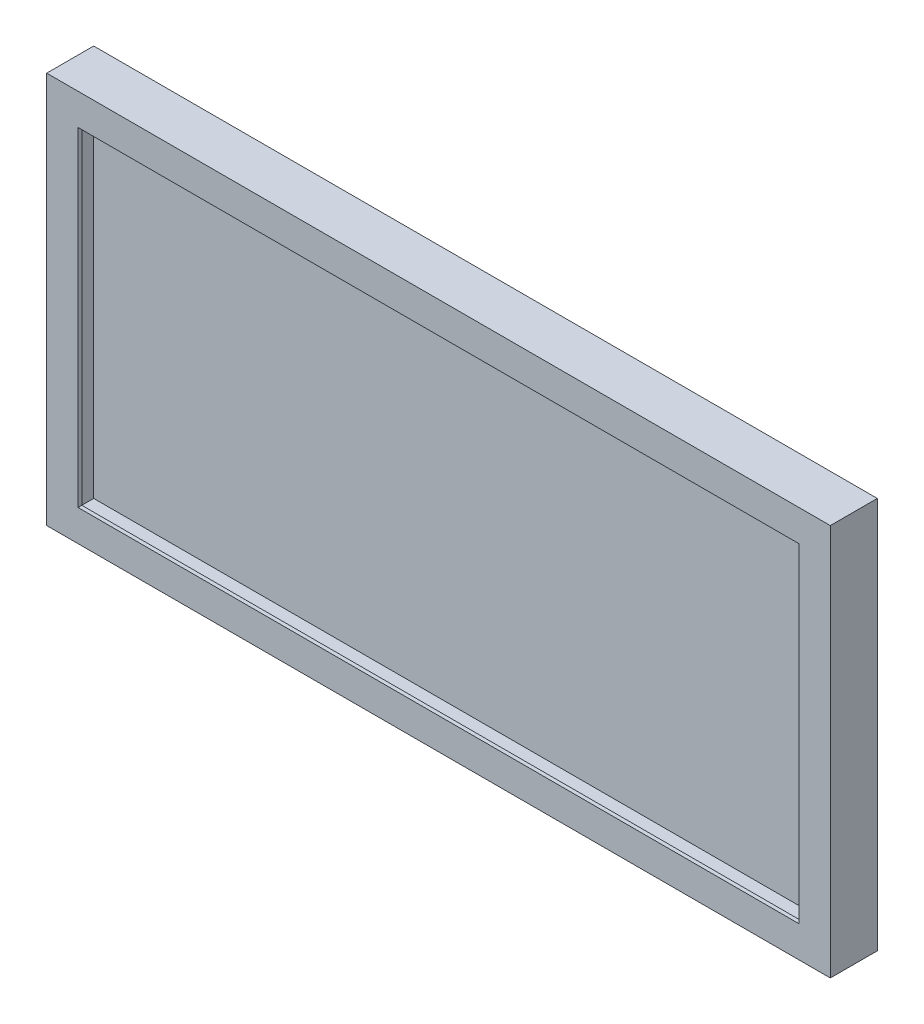
SolidWorks part; units mm, degrees
ref_plane "前视基准面" through (0, 0, 0) normal (0, 0, 1) x (1, 0, 0)
ref_plane "上视基准面" through (0, 0, 0) normal (0, 1, 0) x (1, 0, 0)
ref_plane "右视基准面" through (0, 0, 0) normal (1, 0, 0) x (0, 0, -1)
sketch "草图1" plane through (0, 0, 0) normal (0, 0, 1) x (1, 0, 0)
  line L0 (-125, -62.5) -> (-125, 62.5)
  line L1 (-125, -62.5) -> (125, -62.5)
  line L2 (-125, 62.5) -> (125, 62.5)
  line L3 (125, -62.5) -> (125, 62.5)
  line L4 (-125, -62.5) -> (125, 62.5) construction
  line L5 (-125, 62.5) -> (125, -62.5) construction
  point P1 (0, 0)
  dimension "D1" = 250
  dimension "D2" = 125
extrude "凸台-拉伸1" add sketch "草图1" along normal blind 15
shell "抽壳1" thickness 1.2
sketch "草图3" plane through (0, 0, 15) normal (0, 0, 1) x (1, 0, 0)
  line L14 (115, -52.5) -> (115, 52.5)
  line L15 (-115, -52.5) -> (115, -52.5)
  line L16 (-115, 52.5) -> (-115, -52.5)
  line L17 (115, 52.5) -> (-115, 52.5)
  line L18 (115, -52.5) -> (115, 52.5)
  line L19 (-115, -52.5) -> (115, -52.5)
  line L20 (-115, 52.5) -> (-115, -52.5)
  line L21 (115, 52.5) -> (-115, 52.5)
  dimension "D1" = 10
extrude "切除-拉伸1" cut sketch "草图3" against normal up to next
